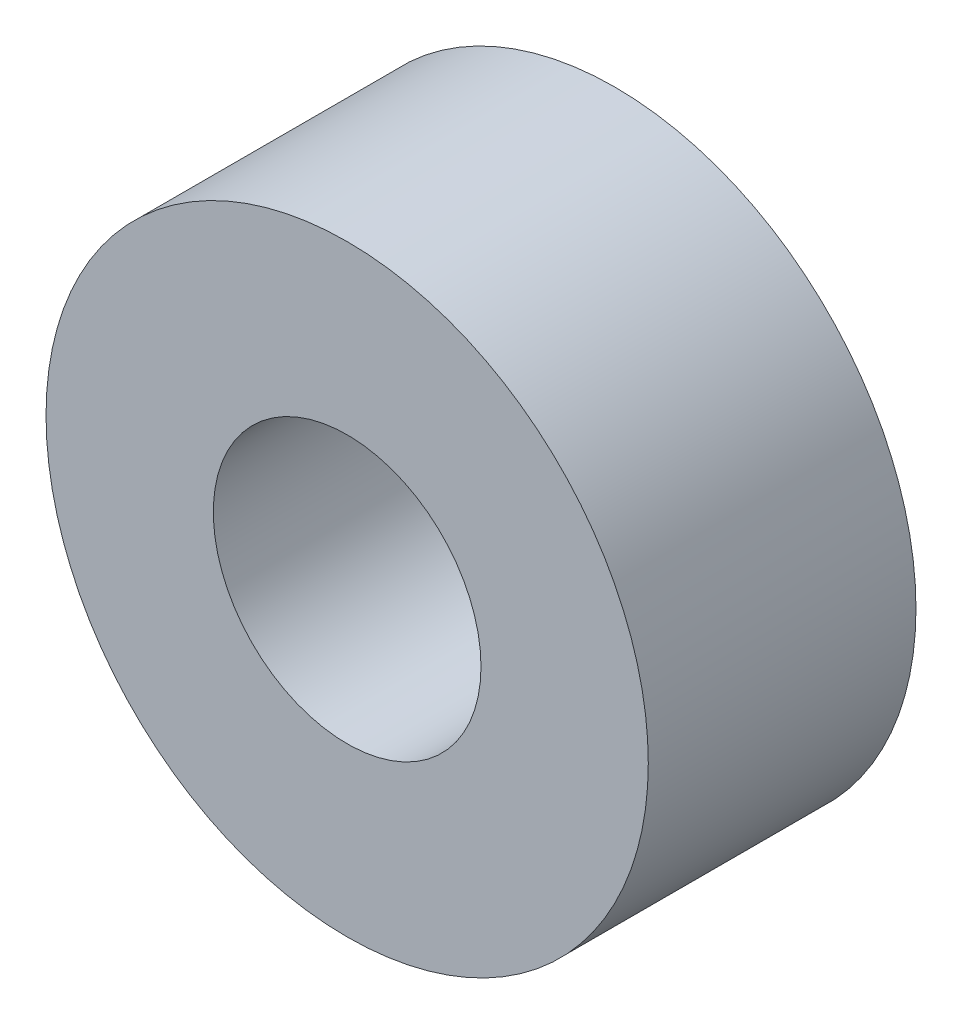
SolidWorks part; units mm, degrees
material "铸造合金钢"
ref_plane "前视基准面" through (0, 0, 0) normal (0, 0, 1) x (1, 0, 0)
ref_plane "上视基准面" through (0, 0, 0) normal (0, 1, 0) x (1, 0, 0)
ref_plane "右视基准面" through (0, 0, 0) normal (1, 0, 0) x (0, 0, -1)
sketch "草图1" plane through (0, 0, 0) normal (0, 0, 1) x (1, 0, 0)
  circle A0 centre (0, 0) radius 4.5
  circle A1 centre (0, 0) radius 2
  dimension "D1" = 9
  dimension "D2" = 4
extrude "凸台-拉伸1" add sketch "草图1" along normal blind 4
